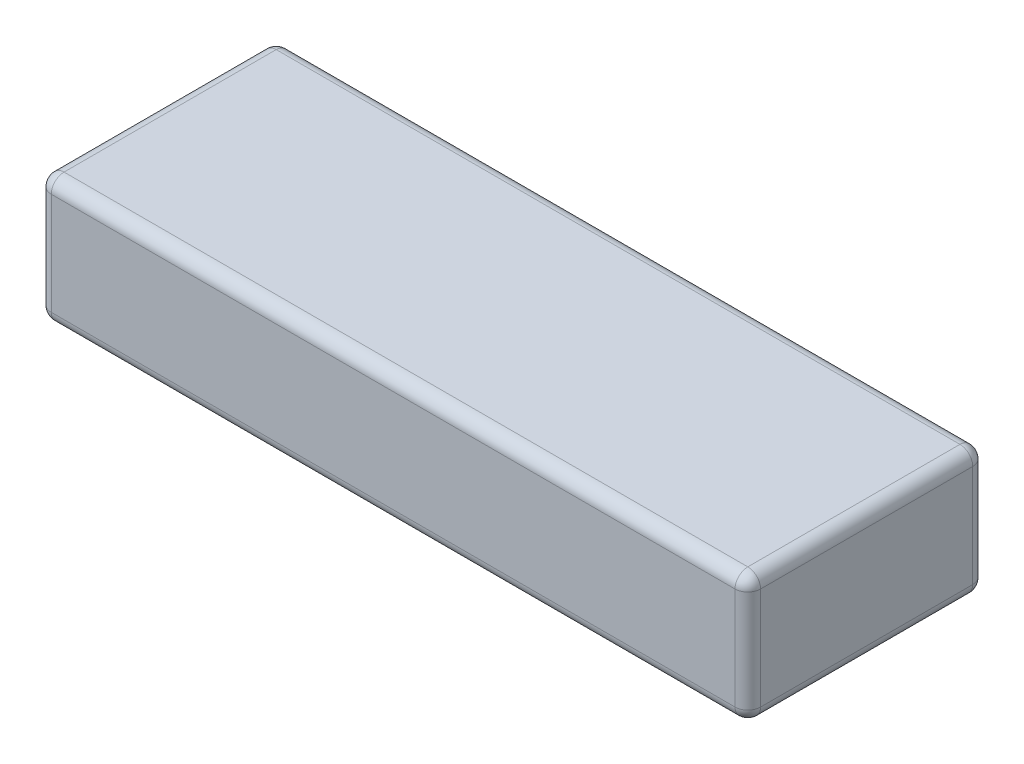
SolidWorks part; units mm, degrees
ref_plane "Front Plane" through (0, 0, 0) normal (0, 0, 1) x (1, 0, 0)
ref_plane "Top Plane" through (0, 0, 0) normal (0, 1, 0) x (1, 0, 0)
ref_plane "Right Plane" through (0, 0, 0) normal (1, 0, 0) x (0, 0, -1)
sketch "Sketch1" plane through (0, 0, 0) normal (1, 0, 0) x (0, 0, -1)
  line L1 (-9.3, 5) -> (9.3, 5)
  line L2 (-9.3, 5) -> (-9.3, -5)
  line L3 (-9.3, -5) -> (9.3, -5)
  line L4 (9.3, 5) -> (9.3, -5)
  line L5 (-9.3, 5) -> (9.3, -5) construction
  line L6 (-9.3, -5) -> (9.3, 5) construction
  point P0 (0, 0)
  dimension "D1" = 18.6
  dimension "D2" = 10
extrude "Boss-Extrude1" add sketch "Sketch1" against normal blind 55.5
fillet "Fillet1" radius 1 4 edges at (-27.75, 5, -9.3) (-27.75, -5, -9.3) (-27.75, -5, 9.3) (-27.75, 5, 9.3)
fillet "Fillet2" radius 1 16 edges at (-55.5, 4.7071, -9.0071) (-55.5, 0, -9.3) (-55.5, -4.7071, -9.0071) (-55.5, -5, 0) (-55.5, -4.7071, 9.0071) (-55.5, 0, 9.3) (-55.5, 4.7071, 9.0071) (0, 4.7071, -9.0071) (0, 0, -9.3) (0, -4.7071, -9.0071) (0, -5, 0) (0, -4.7071, 9.0071) (0, 0, 9.3) (0, 4.7071, 9.0071) (-55.5, 5, 0) (0, 5, 0)
